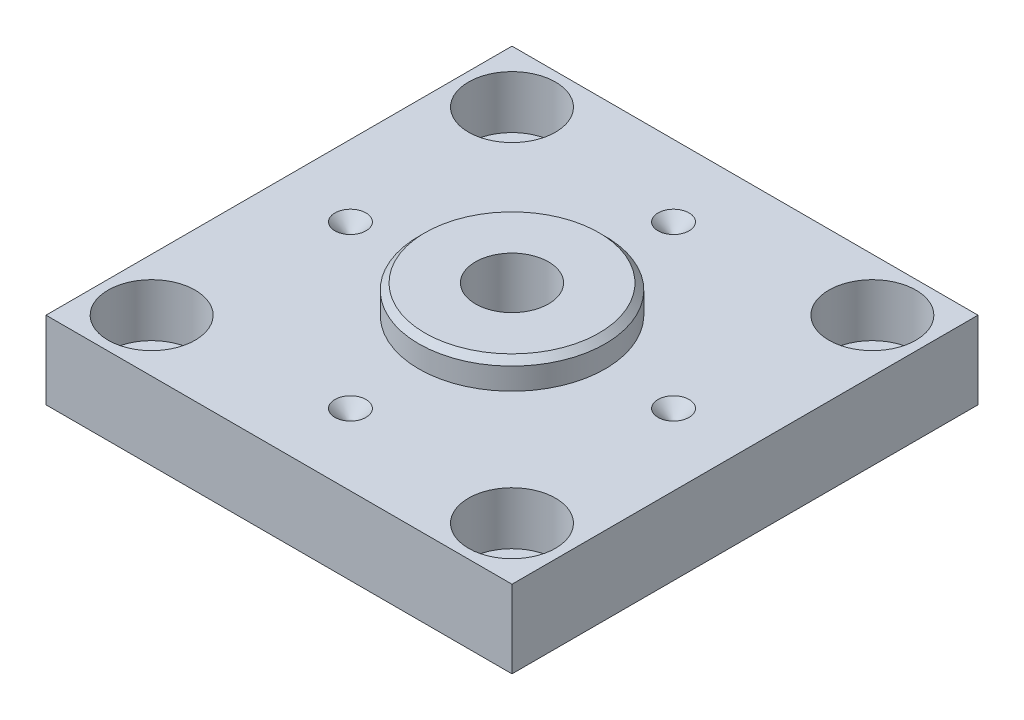
SolidWorks part; units mm, degrees
ref_plane "Front Plane" through (0, 0, 0) normal (0, 0, 1) x (1, 0, 0)
ref_plane "Top Plane" through (0, 0, 0) normal (0, 1, 0) x (1, 0, 0)
ref_plane "Right Plane" through (0, 0, 0) normal (1, 0, 0) x (0, 0, -1)
sketch "Sketch2" plane through (0, 0, 0) normal (0, 1, 0) x (1, 0, 0)
  line L1 (-75, 75) -> (75, 75)
  line L2 (-75, 75) -> (-75, -75)
  line L3 (-75, -75) -> (75, -75)
  line L4 (75, 75) -> (75, -75)
  line L5 (-75, 75) -> (75, -75) construction
  line L6 (-75, -75) -> (75, 75) construction
  point P0 (0, 0)
  dimension "D1" = 150
  dimension "D2" = 150
extrude "Boss-Extrude1" add sketch "Sketch2" along normal blind 25
sketch "Sketch3" plane through (0, 25, 0) normal (0, 1, 0) x (1, 0, 0)
  circle A0 centre (0, 0) radius 30
  dimension "D1" = 60
extrude "Boss-Extrude2" add sketch "Sketch3" along normal blind 9
chamfer "Chamfer1" distance 2 angle 45 1 edges at (0, 34, 30)
sketch "Sketch4" plane through (0, 34, 0) normal (0, 1, 0) x (1, 0, 0)
  circle A0 centre (0, 0) radius 12.5
  dimension "D1" = 25
hole_wizard "Hole1" positions "Sketch11" profile "Sketch12" legacy end condition through all
sketch "Sketch11" plane through (0, 25, 0) normal (0, 1, 0) x (1, 0, 0)
  line L0 (0, 0) -> (-28, 0) construction
  line L2 (0, 0) -> (0, 33.2042) construction
  circle A0 centre (0, 0) radius 28 construction
  point P1 (-58, 58)
  point P3 (58, 58)
  point P5 (58, -58)
  point P7 (-58, 58)
  point P10 (-58, -58)
  dimension "D1" = 116
  dimension "D2" = 116
sketch "Sketch12" plane through (-58, 25, -58) normal (1, 0, 0) x (0, 0, 1)
  line L0 (0, 0) -> (0, 25)
  line L1 (0, 25) -> (8.5, 25)
  line L2 (8.5, 25) -> (8.5, 17)
  line L3 (8.5, 17) -> (14, 17)
  line L4 (14, 17) -> (14, 0)
  line L5 (14, 0) -> (0, 0)
  line L6 (0, 110) -> (0, -10) construction
  dimension "Diameter" = 17
  dimension "Depth" = 25
  dimension "C-Bore Diameter" = 28
  dimension "C-Bore Depth" = 17
sketch "Sketch13" plane through (0, 0, 0) normal (0, 0, 1) x (1, 0, 0)
  line L0 (-57, 25) -> (-52, 20)
  line L1 (-75, 25) -> (75, 25) construction
  line L3 (-52, 25) -> (-57, 25)
  line L4 (-52, 20) -> (-52, 25) construction
  line L5 (-52, 20) -> (-52, 25)
  dimension "D1" = 5
  dimension "D2" = 52
  dimension "D3" = 45
revolve "Cut-Revolve1" cut sketch "Sketch13" angle 360 about L5
hole_wizard "M25x1.5 Tapped Hole1" positions "3DSketch1" profile "Sketch14" tap size "M25x1.5" standard "DIN" end condition through all
sketch3d "3DSketch1"
  point P0 (0, 34, 0)
sketch "Sketch14" plane through (0, 34, 0) normal (1, 0, 0) x (0, 0, 1)
  line L0 (0, 0) -> (0, 34)
  line L1 (0, 34) -> (11.75, 34)
  line L2 (11.75, 34) -> (11.75, 0)
  line L5 (11.75, 0) -> (0, 0)
  line L11 (0, -6.35) -> (0, 107.95) construction
  dimension "Thru Tap Drill Dia." = 23.5
  dimension "Thru Tap Drill Depth" = 34
cosmetic thread "Hole Thread1" parameters "D2"=25
pattern_circular "CirPattern1" count 4 over 360 about axis through (0, 0, 0) along (0, 1, 0) of "Cut-Revolve1"
